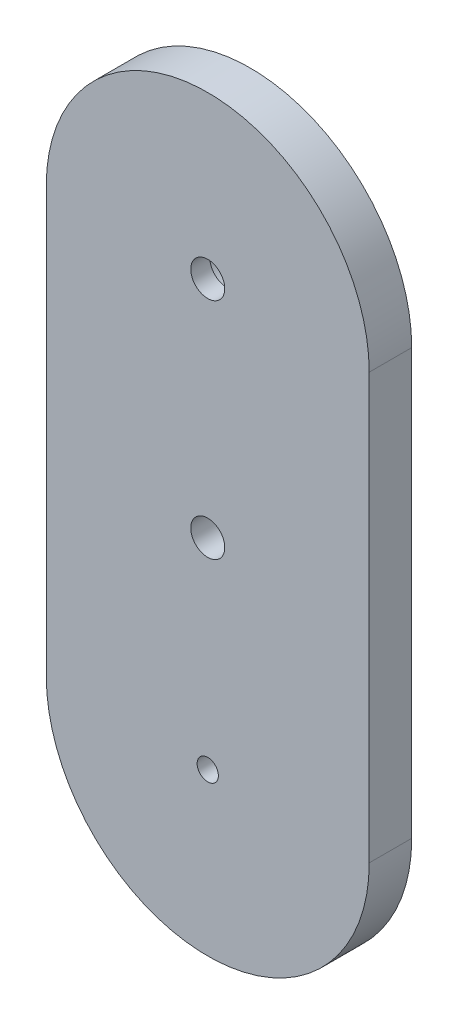
SolidWorks part; units mm, degrees
material "PTEG"
ref_plane "Alzado" through (0, 0, 0) normal (0, 0, 1) x (1, 0, 0)
ref_plane "Planta" through (0, 0, 0) normal (0, 1, 0) x (1, 0, 0)
ref_plane "Vista lateral" through (0, 0, 0) normal (1, 0, 0) x (0, 0, -1)
sketch "Croquis1" plane through (0, 0, 0) normal (0, 0, 1) x (1, 0, 0)
  line L0 (-38, 0) -> (-38, 100)
  line L1 (38, 0) -> (38, 100)
  line L2 (0, 92) -> (0, 2.5) construction
  line L3 (0, 77) -> (-17.5129, 77) construction
  arc A0 (-38, 0) -> (38, 0) centre (0, 0) ccw
  arc A1 (38, 100) -> (-38, 100) centre (0, 100) ccw
  circle A3 centre (0, 0) radius 2.5
  circle A4 centre (0, 100) radius 8
  circle A8 centre (0, 47.25) radius 4
  dimension "D2" = 100
  dimension "D3" = 8
  dimension "D5" = 5
  dimension "D6" = 16
  dimension "D7" = 15
  dimension "D1" = 76
extrude "Saliente-Extruir1" add sketch "Croquis1" along normal blind 10
sketch "Croquis2" plane through (0, 0, 10) normal (0, 0, 1) x (1, 0, 0)
  circle A0 centre (0, 100) radius 8
  circle A1 centre (0, 100) radius 4
  dimension "D1" = 16
  dimension "D2" = 8
extrude "Saliente-Extruir2" add sketch "Croquis2" against normal blind 4.5
